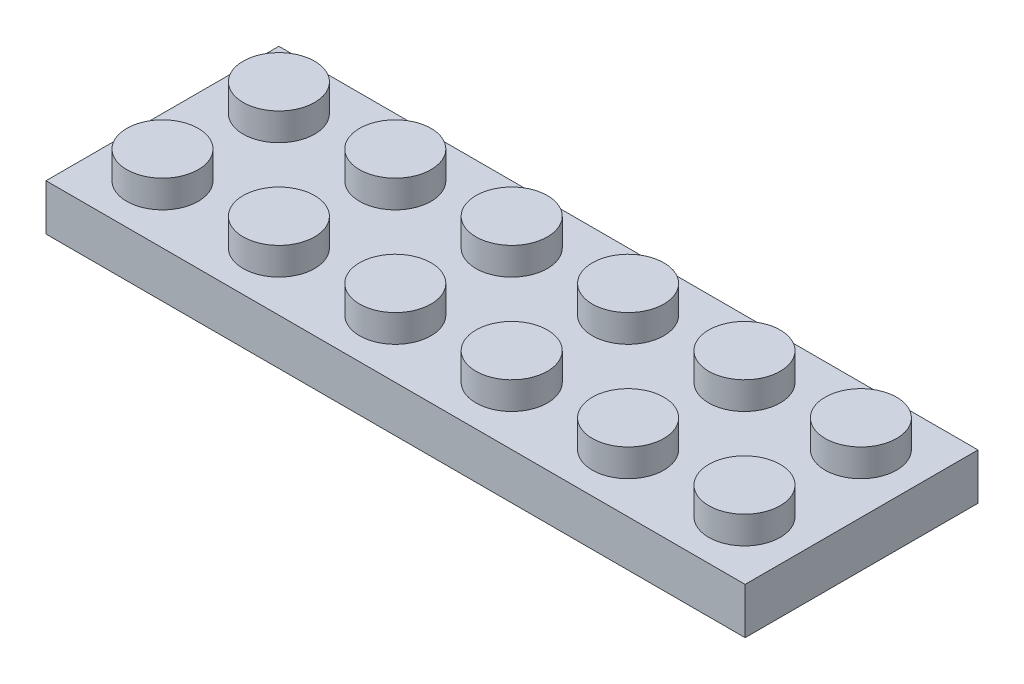
SolidWorks part; units mm, degrees
ref_plane "Front Plane" through (0, 0, 0) normal (0, 0, 1) x (1, 0, 0)
ref_plane "Top Plane" through (0, 0, 0) normal (0, 1, 0) x (1, 0, 0)
ref_plane "Right Plane" through (0, 0, 0) normal (1, 0, 0) x (0, 0, -1)
sketch "Sketch2" plane through (0, 0, 0) normal (0, 1, 0) x (1, 0, 0)
  line L1 (-23.905, 7.9625) -> (23.905, 7.9625)
  line L2 (-23.905, 7.9625) -> (-23.905, -7.9625)
  line L3 (-23.905, -7.9625) -> (23.905, -7.9625)
  line L4 (23.905, 7.9625) -> (23.905, -7.9625)
  line L5 (-23.905, 7.9625) -> (23.905, -7.9625) construction
  line L6 (-23.905, -7.9625) -> (23.905, 7.9625) construction
  point P0 (0, 0)
  dimension "D1" = 47.81
  dimension "D2" = 15.925
extrude "Boss-Extrude1" add sketch "Sketch2" against normal blind 3.16
sketch "Sketch3" plane through (0, 0, 0) normal (0, 1, 0) x (1, 0, 0)
  line L1 (23.905, 7.9625) -> (-23.905, 7.9625) construction
  line L2 (-23.905, 7.9625) -> (-23.905, -7.9625) construction
  circle A0 centre (-19.9208, 3.98) radius 2.445
  circle A1 centre (-11.9608, 3.98) radius 2.445
  circle A2 centre (-4.0008, 3.98) radius 2.445
  circle A3 centre (3.9592, 3.98) radius 2.445
  circle A4 centre (11.9192, 3.98) radius 2.445
  circle A5 centre (19.8792, 3.98) radius 2.445
  circle A6 centre (-11.9608, -3.98) radius 2.445
  circle A7 centre (-4.0008, -3.98) radius 2.445
  circle A8 centre (3.9592, -3.98) radius 2.445
  circle A9 centre (11.9192, -3.98) radius 2.445
  circle A10 centre (19.8792, -3.98) radius 2.445
  circle A11 centre (-19.9208, -3.98) radius 2.445
  dimension "D1" = 4.89
  dimension "D2" = 3.9825
  dimension "D3" = 3.9842
  dimension "D6" = 7.96
  dimension "D7" = 7.96
  dimension "D8" = 3.9842
  dimension "D4" = 6
  dimension "D5" = 2
extrude "Boss-Extrude2" add sketch "Sketch3" along normal blind 1.88
shell "Shell1" thickness 1.45
sketch "Sketch4" plane through (0, -1.45, 0) normal (0, -1, 0) x (1, 0, 0)
  line L1 (-23.905, -7.9625) -> (-23.905, 7.9625) construction
  line L2 (23.905, -7.9625) -> (-23.905, -7.9625) construction
  circle A0 centre (-15.9367, 0.0025) radius 3.15
  circle A1 centre (-15.9367, 0.0025) radius 2.34
  circle A2 centre (-7.9667, 0.0025) radius 2.34
  circle A3 centre (-7.9667, 0.0025) radius 3.15
  circle A4 centre (0.0033, 0.0025) radius 2.34
  circle A5 centre (0.0033, 0.0025) radius 3.15
  circle A6 centre (7.9733, 0.0025) radius 2.34
  circle A7 centre (7.9733, 0.0025) radius 3.15
  circle A8 centre (15.9433, 0.0025) radius 2.34
  circle A9 centre (15.9433, 0.0025) radius 3.15
  dimension "D1" = 6.3
  dimension "D2" = 4.68
  dimension "D3" = 7.9683
  dimension "D4" = 7.965
  dimension "D6" = 7.97
  dimension "D5" = 5
extrude "Boss-Extrude3" add sketch "Sketch4" along normal offset from surface (1.51 mm away) 0.2 up to face at (0, -3.16, 0)
